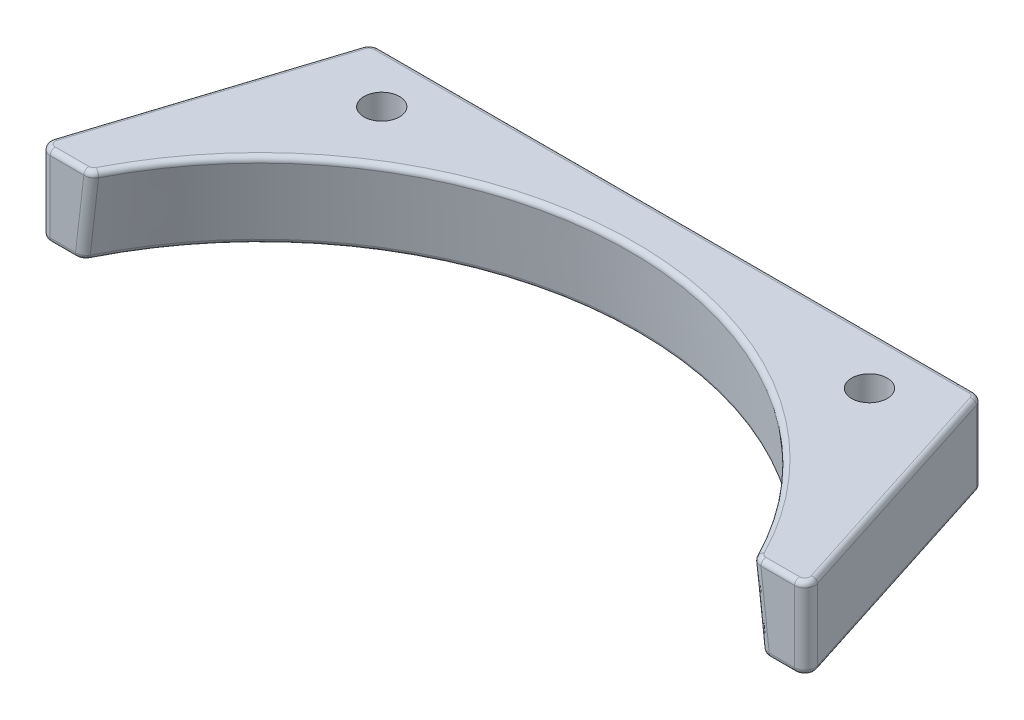
SolidWorks part; units mm, degrees
ref_plane "Front" through (0, 0, 0) normal (0, 0, 1) x (1, 0, 0)
ref_plane "Top" through (0, 0, 0) normal (0, 1, 0) x (1, 0, 0)
ref_plane "Right" through (0, 0, 0) normal (1, 0, 0) x (0, 0, -1)
sketch "Esquisse1" plane through (0, 0, 0) normal (0, 1, 0) x (1, 0, 0)
  line L1 (0, 40) -> (30, 40)
  line L2 (0, 40) -> (0, 15)
  line L3 (0, 15) -> (38, 15)
  line L4 (30, 40) -> (38, 15)
  circle A0 centre (0, 0) radius 36 construction
  circle A1 centre (0, 0) radius 27 construction
  dimension "D1" = 72
  dimension "D2" = 54
  dimension "D3" = 15
  dimension "D4" = 38
  dimension "D5" = 90
  dimension "D6" = 40
  dimension "D7" = 30
extrude "Boss.-Extru.1" add sketch "Esquisse1" against normal blind 8 from offset 35
sketch "Esquisse2" plane through (0, 0, 0) normal (1, 0, 0) x (0, 0, -1)
  line L0 (39, 0) -> (27, 115)
  line L1 (27, 115) -> (-1, 115)
  line L2 (-1, 115) -> (-1, 0)
  line L3 (-1, 0) -> (39, 0)
  line L4 (-1, 115) -> (-1, 143) construction
  dimension "D1" = 39
  dimension "D2" = 115
  dimension "D3" = 27
  dimension "D4" = 1
revolve "Enlèvement de matière-Révolution1" cut sketch "Esquisse2" angle 360 about L4
fillet "Congé1" radius 1 3 edges at (30, 31, -40) (38, 31, -15)
sketch "Esquisse3" plane through (0, 27, 0) normal (0, -1, 0) x (1, 0, 0)
  line L0 (29.27, -40) -> (0, -40) construction
  circle A0 centre (24, -35) radius 1.75
  dimension "D1" = 35
  dimension "D2" = 5
  dimension "D3" = 24
  dimension "D4" = 3.5
extrude "Enlèv. mat.-Extru.1" cut sketch "Esquisse3" against normal through all
sketch "Esquisse4" plane through (0, 27, 0) normal (0, -1, 0) x (1, 0, 0)
  circle A0 centre (24, -35) radius 3.5
  circle A1 centre (24, -35) radius 1.75 construction
  dimension "D1" = 7
extrude "Enlèv. mat.-Extru.2" cut sketch "Esquisse4" against normal blind 3.5
fillet "Congé2" radius 0.5 14 edges at (37.4378, 27, -15.4104) (33.9025, 27, -27.8048) (29.8596, 27, -39.8077) (33.5633, 27, -15.2217) (14.635, 35, -40) (29.8596, 35, -39.8077) (33.9025, 35, -27.8048) (37.4378, 35, -15.4104) (34.9453, 35, -15) (32.8435, 35, -15.0898) (14.635, 27, -40) (19.582, 27, -30.6084) (18.9698, 35, -30.005) (35.4127, 27, -15)
mirror "Symétrie1" about plane through (0, 27, -40) normal (-1, 0, 0) of bodies 104
